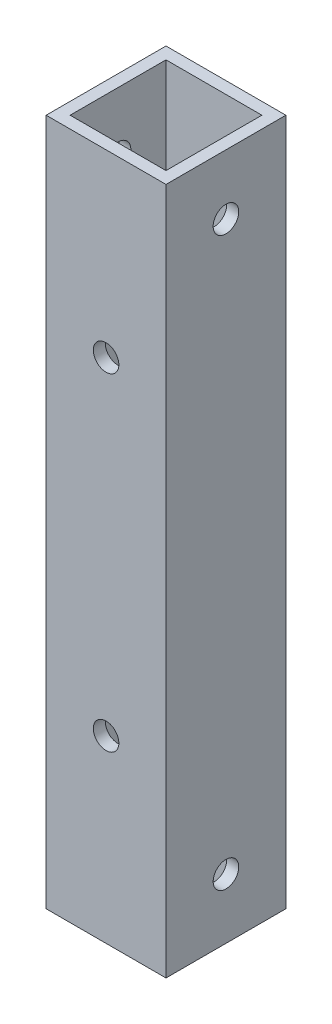
SolidWorks part; units mm, degrees
ref_plane "Front" through (0, 0, 0) normal (0, 0, 1) x (1, 0, 0)
ref_plane "Top" through (0, 0, 0) normal (0, 1, 0) x (1, 0, 0)
ref_plane "Right" through (0, 0, 0) normal (1, 0, 0) x (0, 0, -1)
sketch "ｽｹｯﾁ1" plane through (0, 0, 0) normal (0, 1, 0) x (1, 0, 0)
  line L0 (-6, 6) -> (6, 6)
  line L1 (-7.5, 7.5) -> (7.5, 7.5)
  line L2 (-7.5, 7.5) -> (-7.5, -7.5)
  line L3 (-7.5, -7.5) -> (7.5, -7.5)
  line L4 (7.5, 7.5) -> (7.5, -7.5)
  line L5 (0, -7.5) -> (0, 7.5) construction
  line L6 (-7.5, 0) -> (7.5, 0) construction
  line L7 (6, 6) -> (6, -6)
  line L8 (-6, -6) -> (6, -6)
  line L9 (-6, 6) -> (-6, -6)
  point P0 (0, 0)
  dimension "D1" = 15
  dimension "D2" = 15
  dimension "D3" = 1.5
extrude "ﾎﾞｽ - 押し出し1" add sketch "ｽｹｯﾁ1" along normal blind 86
sketch "ｽｹｯﾁ2" plane through (0, 0, 7.5) normal (0, 0, 1) x (1, 0, 0)
  line L0 (-7.5, 86) -> (-7.5, 0) construction
  line L1 (7.5, 86) -> (7.5, 0) construction
  line L2 (-7.5, 43) -> (7.5, 43) construction
  circle A0 centre (0, 63.5) radius 1.6
  circle A1 centre (0, 22.5) radius 1.6
  point P4 (-7.5, 43)
  point P5 (7.5, 43)
  dimension "D1" = 20.5
  dimension "D3" = 3.2
  dimension "D4" = 3.2
  dimension "D5" = 7.5
  dimension "D6" = 7.5
  dimension "D2" = 20.5
extrude "ｶｯﾄ - 押し出し1" cut sketch "ｽｹｯﾁ2" against normal through all
sketch "ｽｹｯﾁ3" plane through (7.5, 0, 0) normal (1, 0, 0) x (0, 0, -1)
  line L0 (7.5, 86) -> (7.5, 0) construction
  line L1 (-7.5, 0) -> (7.5, 0) construction
  line L2 (-7.5, 86) -> (7.5, 86) construction
  circle A0 centre (0, 78.5) radius 1.6
  circle A1 centre (0, 7.5) radius 1.6
  dimension "D1" = 3.2
  dimension "D2" = 3.2
  dimension "D3" = 7.5
  dimension "D4" = 7.5
  dimension "D5" = 7.5
  dimension "D6" = 7.5
extrude "ｶｯﾄ - 押し出し2" cut sketch "ｽｹｯﾁ3" against normal through all
